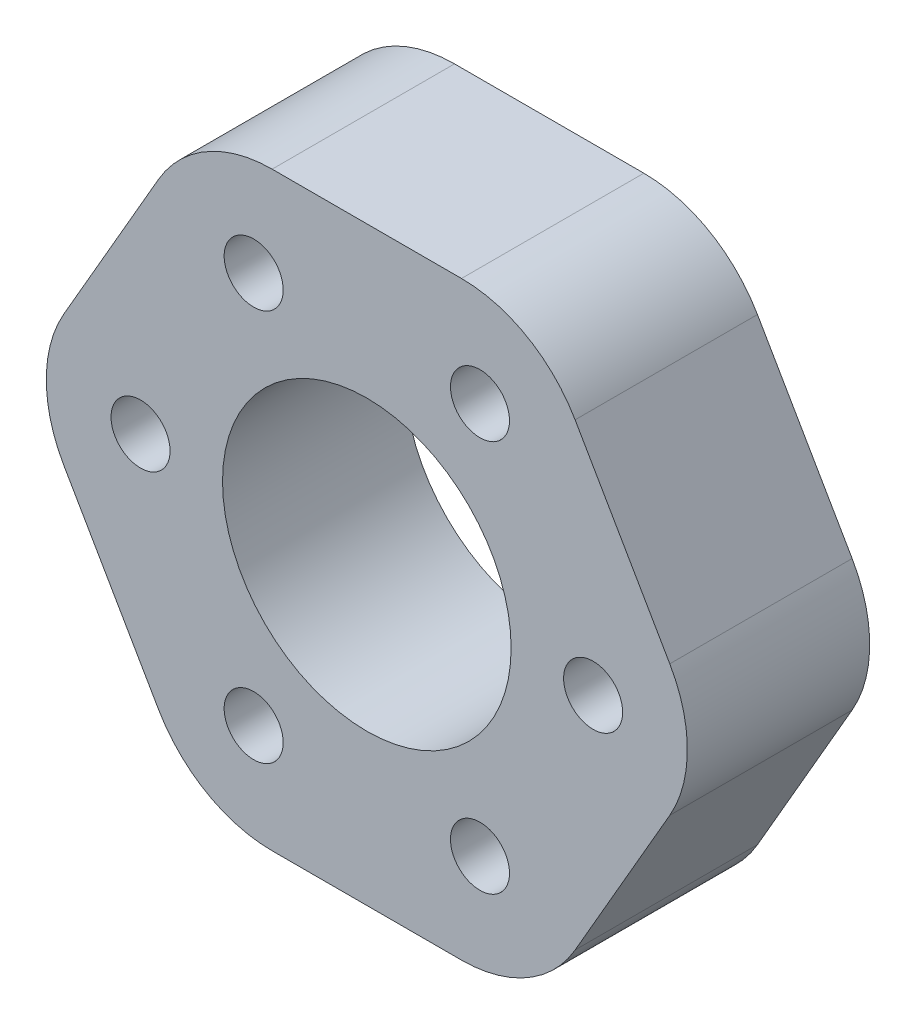
SolidWorks part; units mm, degrees
material "ABS"
ref_plane "前视基准面" through (0, 0, 0) normal (0, 0, 1) x (1, 0, 0)
ref_plane "上视基准面" through (0, 0, 0) normal (0, 1, 0) x (1, 0, 0)
ref_plane "右视基准面" through (0, 0, 0) normal (1, 0, 0) x (0, 0, -1)
sketch "草图1" plane through (0, 0, 0) normal (0, 0, 1) x (1, 0, 0)
  circle A0 centre (0, 0) radius 29.4
  circle A1 centre (0, 0) radius 17.25 construction
  circle A2 centre (-17.25, 0) radius 2.25
  circle A3 centre (-8.625, 14.9389) radius 2.25
  circle A4 centre (8.625, 14.9389) radius 2.25
  circle A5 centre (17.25, 0) radius 2.25
  circle A6 centre (8.625, -14.9389) radius 2.25
  circle A7 centre (-8.625, -14.9389) radius 2.25
  dimension "D1" = 34.5
  dimension "D2" = 4.5
  dimension "D4" = 58.8
  dimension "D3" = 6
extrude "凸台-拉伸1" add sketch "草图1" along normal blind 13.9
sketch "草图2" plane through (0, 0, 13.9) normal (0, 0, 1) x (1, 0, 0)
  line L1 (12.9904, 22.5) -> (-12.9904, 22.5)
  line L2 (-12.9904, 22.5) -> (-25.9808, 0)
  line L3 (-25.9808, 0) -> (-12.9904, -22.5)
  line L4 (-12.9904, -22.5) -> (12.9904, -22.5)
  line L5 (12.9904, -22.5) -> (25.9808, 0)
  line L6 (25.9808, 0) -> (12.9904, 22.5)
  circle A0 centre (0, 0) radius 22.5 construction
  circle A2 centre (0, 0) radius 11
  dimension "D2" = 22
  dimension "D1" = 45
extrude "切除-拉伸1" cut sketch "草图2" against normal through all flip side to cut
fillet "圆角1" radius 10 6 edges at (12.9904, 22.5, 6.95) (-12.9904, 22.5, 6.95) (-25.9808, 0, 6.95) (12.9904, -22.5, 6.95) (25.9808, 0, 6.95) (-12.9904, -22.5, 6.95)
